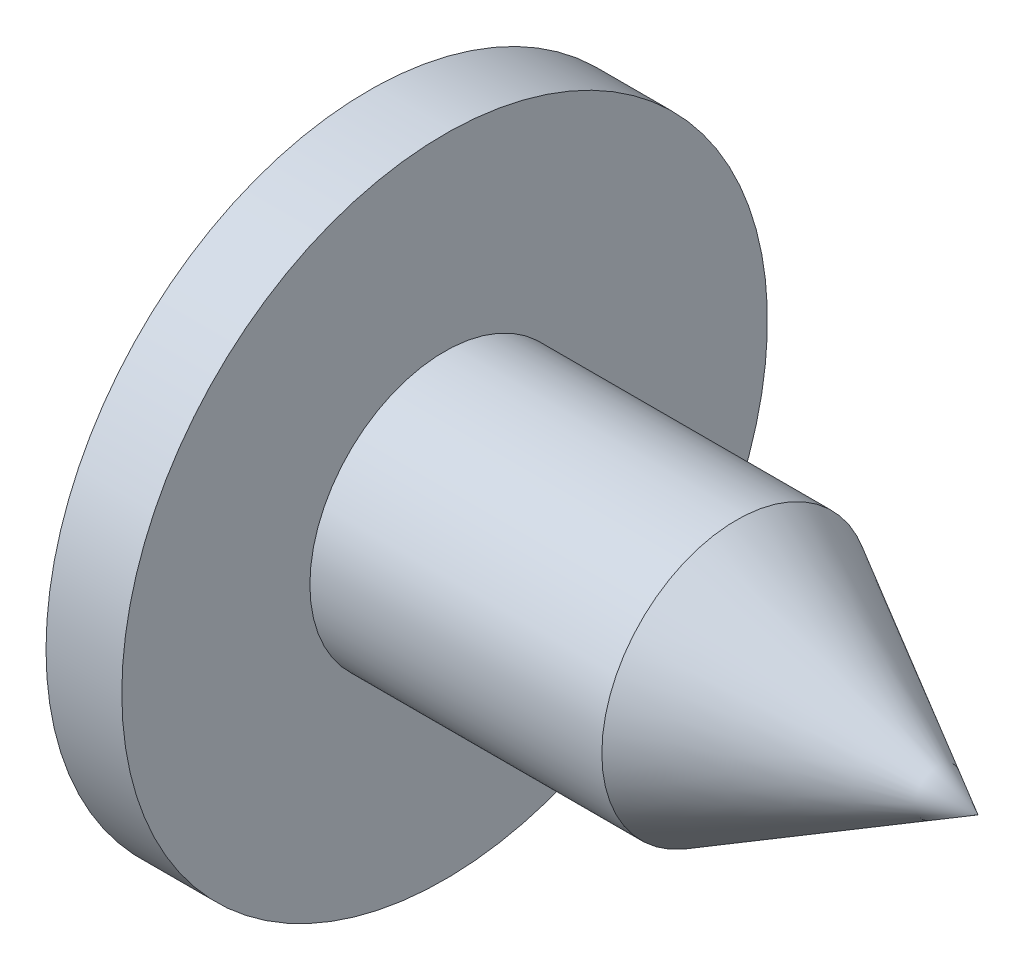
SolidWorks part; units mm, degrees
ref_plane "Front" through (0, 0, 0) normal (0, 0, 1) x (1, 0, 0)
ref_plane "Top" through (0, 0, 0) normal (0, 1, 0) x (1, 0, 0)
ref_plane "Right" through (0, 0, 0) normal (1, 0, 0) x (0, 0, -1)
sketch "Sketch1" plane through (0, 0, 0) normal (0, 0, 1) x (1, 0, 0)
  line L0 (0, 5.75) -> (0, 2.4)
  line L1 (0, 2.4) -> (9.5, 2.4)
  line L2 (9.5, 2.4) -> (9.5, 0)
  line L3 (0, 5.75) -> (-1.35, 5.75)
  line L4 (-1.35, 5.75) -> (-1.35, 4.9193)
  line L5 (-3.55, 0) -> (-3.55, -1.3041) construction
  line L7 (-6.4783, 0) -> (12.5724, 0) construction
  line L8 (-3.55, 0) -> (9.5, 0)
  arc A0 (-1.35, 4.9193) -> (-3.55, 0) centre (3.05, 0) ccw
  dimension "rf" = 6.6
  dimension "k" = 3.55
  dimension "dk" = 11.5
  dimension "c" = 1.35
  dimension "d" = 4.8
  dimension "l" = 9.5
revolve "Revolve1" add sketch "Sketch1" angle 360 about L7
cosmetic thread "ThreadCosmetic" [suppressed] parameters "D2"=3.58
chamfer "Chamfer1" distance 0.48 angle 60 1 edges at (9.5, 0, 2.4)
sketch "Sketch9" plane through (0, 0, 0) normal (0, 0, 1) x (1, 0, 0)
  line L0 (1.4078, 1.79) -> (0.5122, 1.79)
  line L1 (0.5122, 1.79) -> (0.16, 2.4)
  line L2 (1.4078, 1.79) -> (1.76, 2.4)
  line L3 (0.16, 2.4) -> (0.16, 2.65)
  line L4 (1.76, 2.4) -> (1.76, 2.65)
  line L5 (0.16, 2.65) -> (1.76, 2.65)
  line L6 (0.96, 1.79) -> (0.96, 0) construction
  line L7 (0, 0) -> (7.3035, 0) construction
  line L8 (0, -2.4) -> (0, 2.4) construction
  line L10 (0, -5.75) -> (0, 5.75) construction
  line L11 (8.6686, 2.4) -> (0, 2.4) construction
  dimension "D2" = 60
  dimension "D3" = 0.25
  dimension "threadstart" = 0.96
  dimension "minordia" = 3.58
  dimension "advance" = 1.6
revolve "ThreadSchematic" [suppressed] cut sketch "Sketch9" angle 360 about L7
pattern_linear "ThdSchPat" [suppressed] count 6 spacing 1.6 along (1, 0, 0)
sketch "Sketch2" plane through (0, 0, 0) normal (0, 0, 1) x (1, 0, 0)
  line L0 (9.5, 2.4) -> (9.5, 0) construction
  line L1 (9.5, 0) -> (9.5, 1.0614) construction
  line L2 (0, 0) -> (8.4194, 0) construction
  line L5 (9.0765, -0.7059) -> (5.9, -2.4)
  line L7 (5.9, -2.4) -> (5.9, -2.6)
  line L8 (5.9, -2.6) -> (9.7, -2.6)
  line L9 (9.7, -2.6) -> (9.7, 0)
  line L10 (9.7, 0) -> (9.5, 0)
  arc A0 (9.0765, -0.7059) -> (9.5, 0) centre (8.7, 0) ccw
  point P6 (0, -2.4)
  dimension "D1" = 0.8
  dimension "yr" = 3.6
  dimension "D2" = 0.2
  dimension "D3" = 0.2
revolve "EndRound" [suppressed] cut sketch "Sketch2" angle 360 about L2
sketch "Sketch8" plane through (0, 0, 0) normal (0, 0, 1) x (1, 0, 0)
  line L0 (9.5, 0) -> (9.7, 0)
  line L1 (-6.4783, 0) -> (12.5724, 0) construction
  line L2 (9.7, 0) -> (9.7, -2.6)
  line L3 (9.7, -2.6) -> (5.2, -2.6)
  line L4 (5.2, -2.6) -> (5.2, -2.4)
  line L6 (5.2, -2.4) -> (9.5, 0)
  line L7 (0, 0) -> (9.5575, 0) construction
  line L8 (0, -2.4) -> (11.5982, -2.4) construction
  dimension "yc" = 4.3
  dimension "D2" = 0.2
  dimension "D3" = 0.2
revolve "EndCone" cut sketch "Sketch8" angle 360 about L7
ref_plane "Plane1" through (-3.55, 0, 0) normal (1, 0, 0) x (0, 0, -1)
sketch "Sketch4" plane through (-3.55, 0, 0) normal (1, 0, 0) x (0, 0, -1)
  line L0 (0.5, 2.5) -> (-0.5, 2.5)
  line L1 (-0.5, 2.5) -> (-0.5, 0.5)
  line L2 (-0.5, 0.5) -> (-2.5, 0.5)
  line L3 (-2.5, 0.5) -> (-2.5, -0.5)
  line L4 (-2.5, -0.5) -> (-0.5, -0.5)
  line L5 (-0.5, -0.5) -> (-0.5, -2.5)
  line L6 (-0.5, -2.5) -> (0.5, -2.5)
  line L7 (0.5, -2.5) -> (0.5, -0.5)
  line L8 (0.5, -0.5) -> (2.5, -0.5)
  line L9 (2.5, -0.5) -> (2.5, 0.5)
  line L10 (2.5, 0.5) -> (0.5, 0.5)
  line L11 (0.5, 0.5) -> (0.5, 2.5)
  line L12 (2.5, 0) -> (-2.5, 0) construction
  dimension "m" = 5
  dimension "D2" = 1
extrude "Cut-Extrude1" cut sketch "Sketch4" along normal blind 2.28
draft "Draft1" type of draft neutral plane draft angle 35 neutral plane "Plane1" faces to draft 4 face at (-2.159, 0, -2.5) face at (-2.159, -2.5, 0) face at (-2.159, 0, 2.5) face at (-2.159, 2.5, 0) neutral plane through (-3.55, 0, 0) neutral plane normal (1, 0, 0) reverse direction yes parameters "D1"=35
draft "Draft2" type of draft neutral plane draft angle 8 neutral plane "Plane1" faces to draft 8 face at (-2.3139, 1.0333, -0.5) face at (-2.3139, 0.5, -1.0333) face at (-2.3139, -0.5, -1.0333) face at (-2.3139, -1.0333, -0.5) face at (-2.3139, -1.0333, 0.5) face at (-2.3139, -0.5, 1.0333) face at (-2.3139, 0.5, 1.0333) face at (-2.3139, 1.0333, 0.5) neutral plane through (-3.55, 0, 0) neutral plane normal (1, 0, 0) reverse direction yes parameters "D1"=8
fillet "Fillet1" radius 0.4167 4 edges at (-2.3914, -0.3372, -0.3372) (-2.3914, -0.3372, 0.3372) (-2.3914, 0.3372, 0.3372) (-2.3914, 0.3372, -0.3372)
sketch "Sketch7" plane through (-3.55, 0, 0) normal (1, 0, 0) x (0, 0, -1)
  line L0 (-0.4437, 2.2197) -> (-2.2197, 2.2197) construction
  line L1 (-2.2197, 2.2197) -> (-2.2197, 0.4437) construction
  line L2 (0, 0) -> (-2.2197, 2.2197) construction
  line L3 (-0.1796, 0.5922) -> (-2.2197, 2.2197)
  line L4 (-2.2197, 2.2197) -> (-0.5922, 0.1796)
  line L5 (-0.5922, 0.1796) -> (-0.5922, 0)
  line L6 (-0.1796, 0.5922) -> (0, 0.5922)
  line L7 (0.1796, 0.5922) -> (0, 0.5922)
  line L8 (2.2197, 2.2197) -> (0.1796, 0.5922)
  line L9 (0.5922, 0.1796) -> (2.2197, 2.2197)
  line L10 (0.5922, 0.1796) -> (0.5922, 0)
  line L11 (0.5922, -0.1796) -> (0.5922, 0)
  line L12 (2.2197, -2.2197) -> (0.5922, -0.1796)
  line L13 (0.1796, -0.5922) -> (2.2197, -2.2197)
  line L14 (0.1796, -0.5922) -> (0, -0.5922)
  line L15 (-0.1796, -0.5922) -> (0, -0.5922)
  line L16 (-2.2197, -2.2197) -> (-0.1796, -0.5922)
  line L17 (-0.5922, -0.1796) -> (-2.2197, -2.2197)
  line L18 (-0.5922, -0.1796) -> (-0.5922, 0)
extrude "TypeZ" [suppressed] cut sketch "Sketch7" along normal blind 0.456 draft 2
equation "\"minordia@Sketch9\" = \"D2@ThreadCosmetic\""
equation "\"D1@Chamfer1\" = \"d@Sketch1\" / 10"
equation "\"D1@Sketch2\" = \"d@Sketch1\" / 6"
equation "\"D2@Sketch4\" = \"m@Sketch4\" / 5"
equation "\"D1@TypeZ\" = \"depth@Cut-Extrude1\" * 0.2"
equation "\"D1@Fillet1\" =\"m@Sketch4\" /12"
equation "\"threadstart@Sketch9\" = \"advance@Sketch9\" * 0.6"
equation "\"D1@ThdSchPat\" = int((\"l@Sketch1\"/\"advance@Sketch9\") + 0.999)"
equation "\"D3@ThdSchPat\" = \"advance@Sketch9\""
